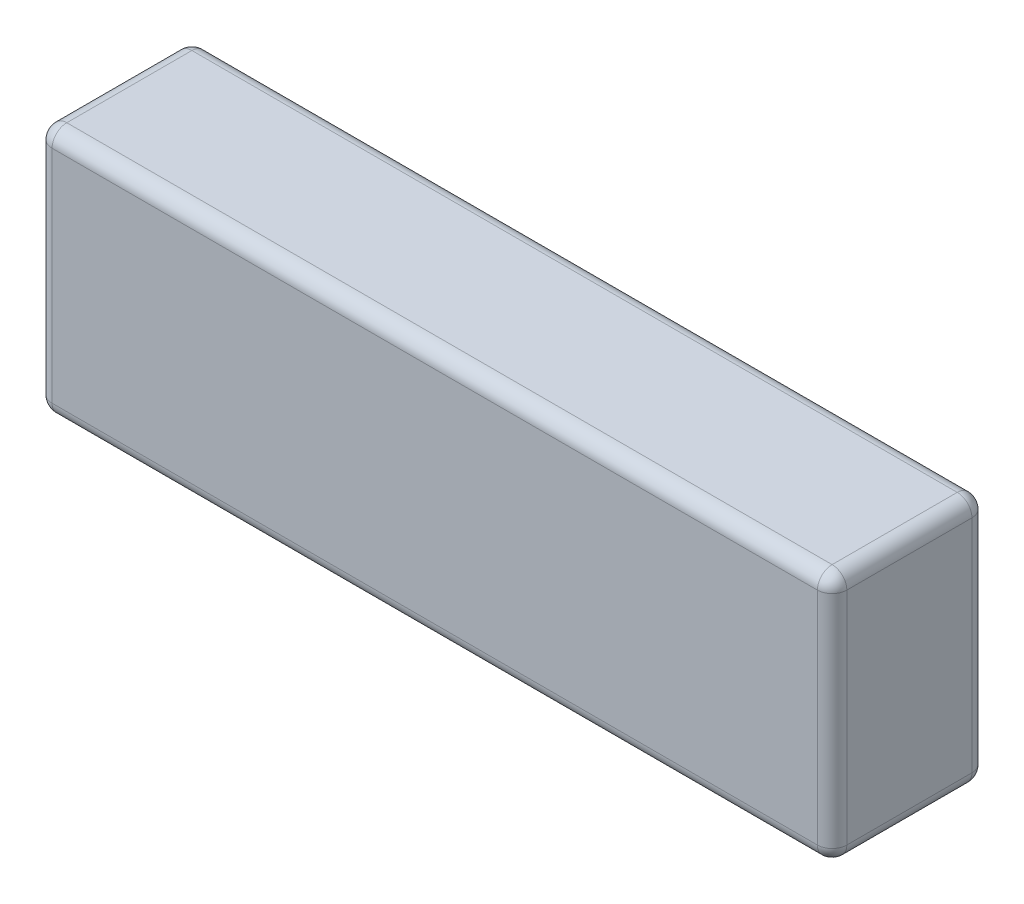
SolidWorks part; units mm, degrees
material "ABS"
ref_plane "Front Plane" through (0, 0, 0) normal (0, 0, 1) x (1, 0, 0)
ref_plane "Top Plane" through (0, 0, 0) normal (0, 1, 0) x (1, 0, 0)
ref_plane "Right Plane" through (0, 0, 0) normal (1, 0, 0) x (0, 0, -1)
sketch "Sketch1" plane through (0, 0, 0) normal (0, 0, 1) x (1, 0, 0)
  line L1 (-54, -17) -> (54, -17)
  line L2 (-54, -17) -> (-54, 17)
  line L3 (-54, 17) -> (54, 17)
  line L4 (54, -17) -> (54, 17)
  line L5 (-54, -17) -> (54, 17) construction
  line L6 (-54, 17) -> (54, -17) construction
  point P0 (0, 0)
  dimension "D1" = 34
  dimension "D2" = 108
extrude "Boss-Extrude1" add sketch "Sketch1" along normal blind 21
fillet "Fillet1" radius 2 12 edges at (54, 17, 10.5) (-54, 17, 10.5) (0, 17, 0) (-54, 0, 0) (54, 0, 0) (-54, -17, 10.5) (54, -17, 10.5) (0, -17, 0) (0, -17, 21) (-54, 0, 21) (0, 17, 21) (54, 0, 21)
